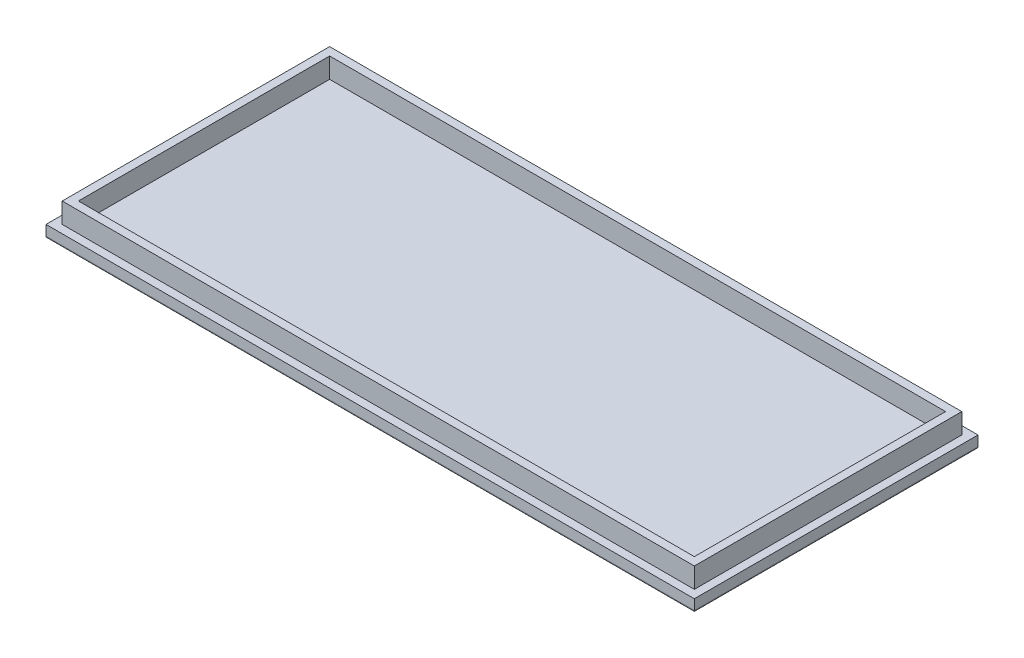
SolidWorks part; units mm, degrees
ref_plane "정면" through (0, 0, 0) normal (0, 0, 1) x (1, 0, 0)
ref_plane "윗면" through (0, 0, 0) normal (0, 1, 0) x (1, 0, 0)
ref_plane "우측면" through (0, 0, 0) normal (1, 0, 0) x (0, 0, -1)
sketch "스케치1" plane through (0, 0, 0) normal (0, 1, 0) x (1, 0, 0)
  line L1 (78, -33) -> (-78, -33)
  line L2 (-78, -33) -> (-78, 33)
  line L3 (-78, 33) -> (78, 33)
  line L4 (80, -35) -> (-80, -35)
  line L6 (-80, 35) -> (80, 35)
  line L7 (-80, -35) -> (-80, 35)
  line L8 (-80, 0) -> (0, 0) construction
  line L9 (0, 35) -> (0, -35) construction
  line L10 (78, -33) -> (78, 33)
  line L11 (80, -35) -> (80, 35)
  point P1 (0, -33)
  point P6 (0, 33)
  point P12 (0, 0)
  dimension "D1" = 160
  dimension "D2" = 70
  dimension "D3" = 156
extrude "보스-돌출1" add sketch "스케치1" along normal blind 3
sketch "스케치2" plane through (0, 3, 0) normal (0, 1, 0) x (1, 0, 0)
  line L0 (78, -33) -> (78, 33) construction
  line L1 (78, 33) -> (-78, 33) construction
  line L2 (-78, -33) -> (78, -33) construction
  line L3 (-78, 33) -> (-78, -33) construction
  line L4 (78, -33) -> (78, 33)
  line L5 (78, 33) -> (-78, 33)
  line L6 (-78, -33) -> (78, -33)
  line L7 (-78, 33) -> (-78, -33)
extrude "보스-돌출2" add sketch "스케치2" along normal blind 5 and the other way up to vertex (3 mm away) other way up to point (-80, 0, 35)
sketch "스케치3" plane through (0, 8, 0) normal (0, 1, 0) x (1, 0, 0)
  line L8 (-76, -31) -> (76, -31)
  line L9 (76, -31) -> (76, 31)
  line L10 (76, 31) -> (-76, 31)
  line L11 (-76, 31) -> (-76, -31)
  line L12 (-76, -31) -> (76, -31)
  line L13 (76, -31) -> (76, 31)
  line L14 (76, 31) -> (-76, 31)
  line L15 (-76, 31) -> (-76, -31)
  dimension "D1" = 2
extrude "컷-돌출1" cut sketch "스케치3" against normal up to vertex (5 mm away) up to point (-78, 3, 33)
fillet "필렛1" radius 0.5 4 edges at (-80, 0, 0) (80, 0, 0) (0, 0, 35) (0, 0, -35)
